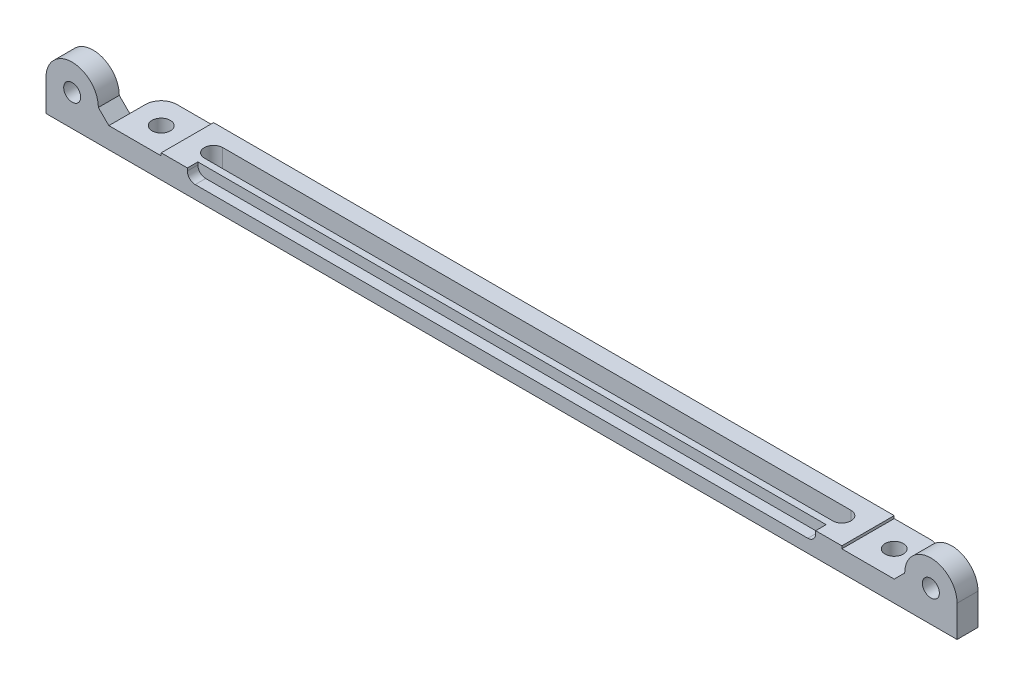
SolidWorks part; units mm, degrees
ref_plane "Front Plane" through (0, 0, 0) normal (0, 0, 1) x (1, 0, 0)
ref_plane "Top Plane" through (0, 0, 0) normal (0, 1, 0) x (1, 0, 0)
ref_plane "Right Plane" through (0, 0, 0) normal (1, 0, 0) x (0, 0, -1)
sketch "Sketch1" plane through (0, 0, 0) normal (0, 1, 0) x (1, 0, 0)
  line L1 (72, 5) -> (-72, 5)
  line L2 (75, 2) -> (75, -5)
  line L3 (75, -5) -> (-75, -5)
  line L4 (-75, 2) -> (-75, -5)
  line L5 (75, 5) -> (-75, -5) construction
  line L6 (75, -5) -> (-75, 5) construction
  line L7 (60, -1.75) -> (-60, -1.75)
  line L8 (60, -1.75) -> (60, 1.75)
  line L9 (60, 1.75) -> (-60, 1.75)
  line L10 (-60, -1.75) -> (-60, 1.75)
  line L11 (60, -1.75) -> (-60, 1.75) construction
  line L12 (60, 1.75) -> (-60, -1.75) construction
  circle A0 centre (-70, 0) radius 1.75
  circle A1 centre (70, 0) radius 1.75
  arc A2 (75, 2) -> (72, 5) centre (72, 2) ccw
  arc A3 (-72, 5) -> (-75, 2) centre (-72, 2) ccw
  circle A4 centre (-60, 0) radius 1.75
  circle A5 centre (60, 0) radius 1.75
  point P0 (0, 0)
  point P16 (0, 0)
  dimension "D3" = 3.5
  dimension "D6" = 3.5
  dimension "D9" = 3
  dimension "D10" = 3
  dimension "D1" = 10
  dimension "D2" = 150
  dimension "D4" = 5
  dimension "D5" = 5
  dimension "D7" = 5
  dimension "D8" = 5
  dimension "D11" = 3.5
  dimension "D12" = 120
extrude "Boss-Extrude1" add sketch "Sketch1" along normal blind 4 contours L1 A3 L4 L3 L2 A2 A5 L7 A4 L9 A0 A1
sketch "Sketch2" plane through (0, 4, 0) normal (0, 1, 0) x (1, 0, 0)
  line L0 (72, 5) -> (-72, 5) construction
  line L1 (-65, 5) -> (65, 5)
  line L2 (-65, 5) -> (-65, -5)
  line L3 (-65, -5) -> (65, -5)
  line L4 (65, 5) -> (65, -5)
  line L5 (75, -5) -> (-75, -5) construction
  line L6 (-75, 2) -> (-75, -5) construction
  line L7 (75, 2) -> (75, -5) construction
  line L12 (72, 5) -> (-72, 5)
  line L13 (-75, 2) -> (-75, -5)
  line L14 (-75, -5) -> (75, -5)
  line L15 (75, -5) -> (75, 2)
  line L16 (72, 5) -> (-72, 5)
  line L17 (-75, 2) -> (-75, -5)
  line L18 (-75, -5) -> (75, -5)
  line L19 (75, -5) -> (75, 2)
  arc A2 (-72, 5) -> (-75, 2) centre (-72, 2) ccw
  arc A3 (75, 2) -> (72, 5) centre (72, 2) ccw
  arc A4 (-72, 5) -> (-75, 2) centre (-72, 2) ccw
  arc A5 (75, 2) -> (72, 5) centre (72, 2) ccw
  arc M11 (60, 1.75) -> (60, -1.75) centre (60, 0) cw
  line M12 (60, -1.75) -> (-60, -1.75)
  arc M13 (-60, -1.75) -> (-60, 1.75) centre (-60, 0) cw
  line M14 (-60, 1.75) -> (60, 1.75)
  line M17 (72, 5) -> (-72, 5)
  line M20 (-75, -5) -> (75, -5)
  dimension "D1" = 10
  dimension "D2" = 10
  dimension "D3" = 0
extrude "Boss-Extrude2" add sketch "Sketch2" along normal blind 0.5 contours L4 L2 M17 M20 M14 M11 M12 M13
sketch "Sketch3" plane through (0, 0, 5) normal (0, 0, 1) x (1, 0, 0)
  line L0 (0, 4.5) -> (0, 0) construction
  line L7 (-65, 4.5) -> (65, 4.5) construction
  line L9 (58.5, 2.5) -> (-58.5, 2.5)
  line L10 (60, 4) -> (60, 4.5)
  line L11 (60, 4.5) -> (-60, 4.5)
  line L12 (-60, 4) -> (-60, 4.5)
  line L13 (60, 2.5) -> (-60, 4.5) construction
  line L14 (60, 4.5) -> (-60, 2.5) construction
  arc A2 (-58.5, 2.5) -> (-60, 4) centre (-58.5, 4) cw
  arc A3 (58.5, 2.5) -> (60, 4) centre (58.5, 4) ccw
  point P5 (0, 3.5)
  dimension "D3" = 1.5
  dimension "D4" = 1.5
  dimension "D1" = 2
  dimension "D2" = 120
extrude "Cut-Extrude1" cut sketch "Sketch3" against normal blind 2
sketch "Sketch4" plane through (0, 0, 5) normal (0, 0, 1) x (1, 0, 0)
  line L0 (-75, 0) -> (-87, 0)
  line L1 (-87, 0) -> (-87, 6)
  line L2 (-75, 4) -> (-77, 6)
  line L3 (0, 0) -> (0, 2.5) construction
  line L6 (75, 4) -> (77, 6)
  line L7 (87, 0) -> (87, 6)
  line L8 (75, 0) -> (87, 0)
  line L9 (75, 0) -> (-75, 0) construction
  line L10 (-58.5, 2.5) -> (58.5, 2.5) construction
  arc A0 (-77, 6) -> (-87, 6) centre (-82, 6) ccw
  circle A1 centre (-82, 6) radius 1.6242
  circle A2 centre (82, 6) radius 1.6242
  arc A3 (77, 6) -> (87, 6) centre (82, 6) cw
  line M7 (75, 0) -> (75, 4)
  line M13 (-75, 4) -> (-75, 0)
  dimension "D1" = 12
  dimension "D2" = 6
  dimension "D3" = 5
extrude "Boss-Extrude3" add sketch "Sketch4" against normal blind 4 contours L2 A0 L1 L0 A1 M13 | A3 L6 L8 L7 A2 M7
